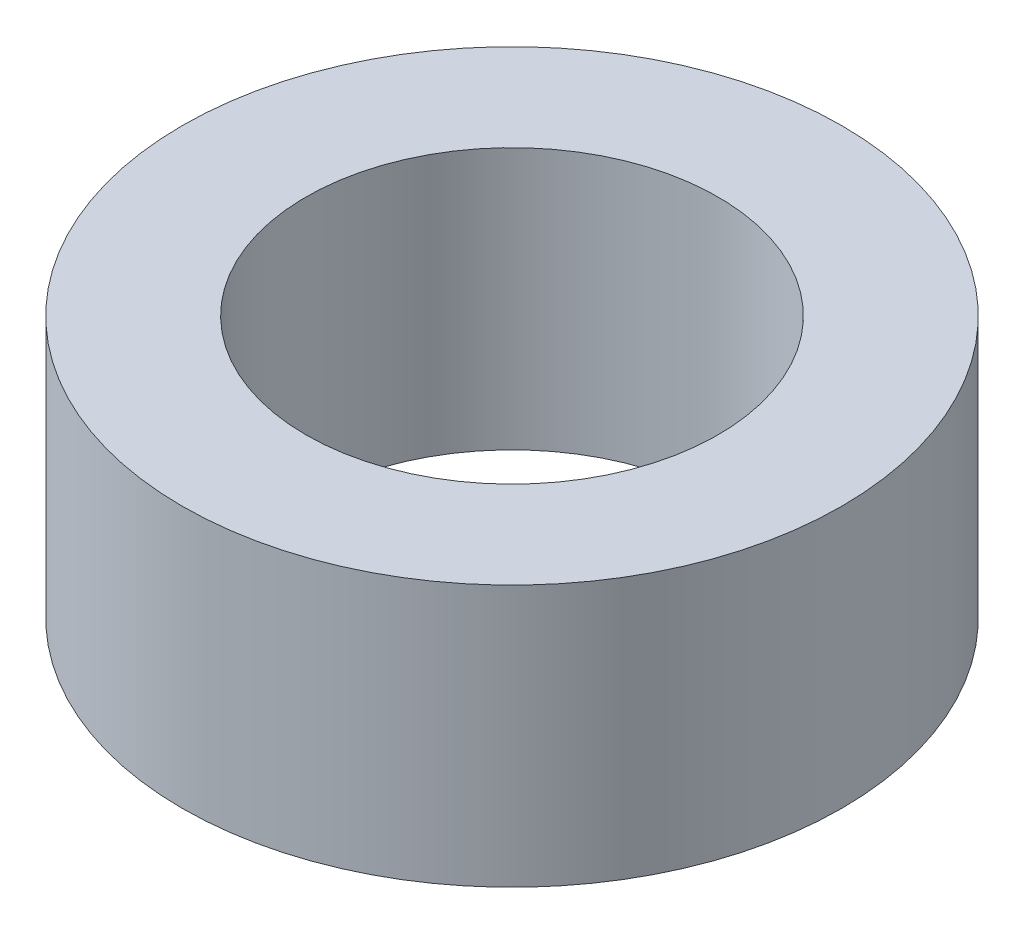
SolidWorks part; units mm, degrees
material "Nylon 101"
ref_plane "Front Plane" through (0, 0, 0) normal (0, 0, 1) x (1, 0, 0)
ref_plane "Top Plane" through (0, 0, 0) normal (0, 1, 0) x (1, 0, 0)
ref_plane "Right Plane" through (0, 0, 0) normal (1, 0, 0) x (0, 0, -1)
sketch "Sketch2" plane through (0, 0, 0) normal (0, 1, 0) x (1, 0, 0)
  circle A0 centre (0, 0) radius 2.5
  circle A1 centre (0, 0) radius 4
  dimension "D1" = 5
  dimension "D2" = 8
extrude "Boss-Extrude1" add sketch "Sketch2" along normal blind 3.175
